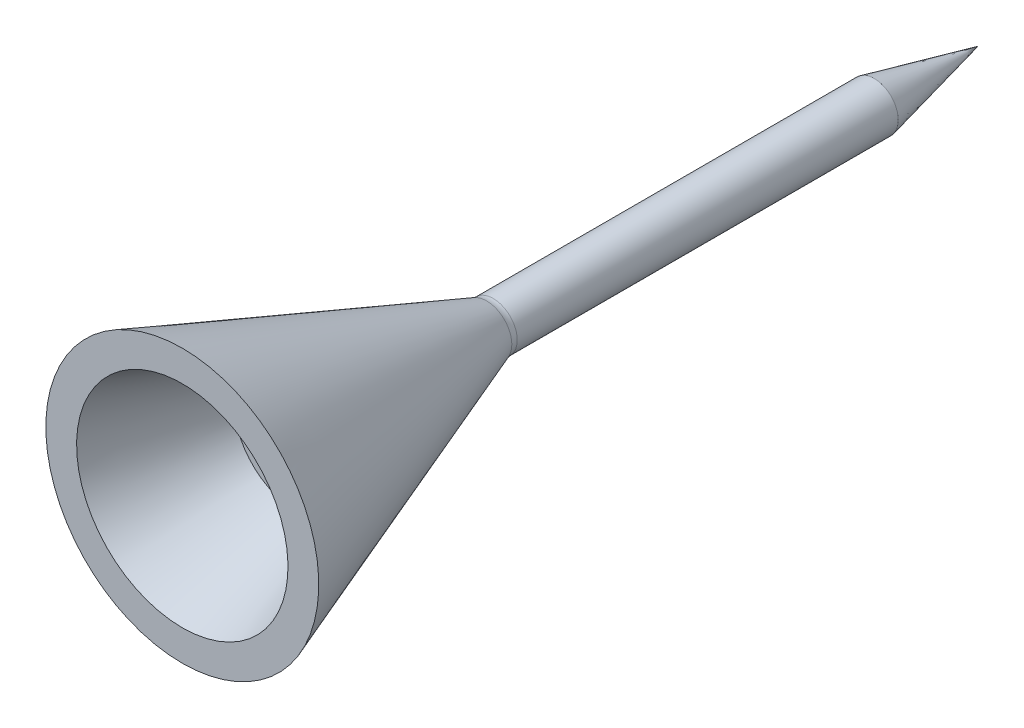
SolidWorks part; units mm, degrees
ref_plane "Front Plane" through (0, 0, 0) normal (0, 0, 1) x (1, 0, 0)
ref_plane "Top Plane" through (0, 0, 0) normal (0, 1, 0) x (1, 0, 0)
ref_plane "Right Plane" through (0, 0, 0) normal (1, 0, 0) x (0, 0, -1)
sketch "Sketch1" plane through (0, 0, 0) normal (1, 0, 0) x (0, 0, -1)
  line L0 (-16, 5.85) -> (-16, 4.25)
  line L1 (-16, 4.25) -> (-10, 2.0562)
  line L2 (-10, 2.0562) -> (-10, 0)
  line L3 (-10, 0) -> (-4.3761, 0)
  line L4 (-4.3761, 0) -> (-10, 2.0562)
  line L5 (-16, 5.85) -> (0, 0)
  line L6 (0, 0) -> (-4.3761, 0)
  line L7 (-24, 0) -> (-10, 0) construction
  line L8 (20, 0) -> (25.4, -1.25)
  line L9 (-10, 0) -> (20, 0)
  line L10 (-10, 0) -> (-10, -1.25)
  line L11 (-10, -1.25) -> (20, -1.25)
  line L12 (20, 0) -> (20, -1.25)
  line L13 (25.4, -1.25) -> (20, -1.25)
  dimension "D1" = 7.1
  dimension "D2" = 24
  dimension "D3" = 20
  dimension "D4" = 1.25
  dimension "D5" = 1.6
  dimension "D6" = 5.4
  dimension "D7" = 30
  dimension "D8" = 16
revolve "Revolve1" add sketch "Sketch1" angle 360 about L11
fillet "Fillet1" radius 1 1 edges at (0, -2.5, 0)
